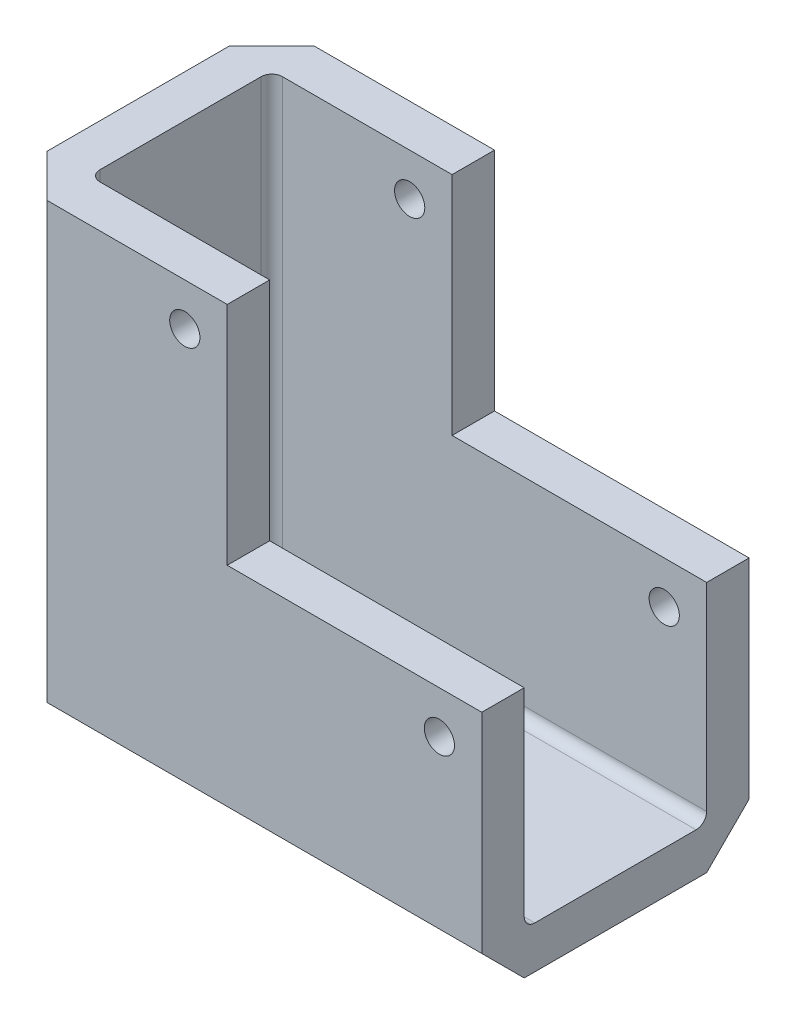
SolidWorks part; units mm, degrees
ref_plane "Alzado" through (0, 0, 0) normal (0, 0, 1) x (1, 0, 0)
ref_plane "Planta" through (0, 0, 0) normal (0, 1, 0) x (1, 0, 0)
ref_plane "Vista lateral" through (0, 0, 0) normal (1, 0, 0) x (0, 0, -1)
sketch "Croquis1" plane through (0, 0, 0) normal (0, 0, 1) x (1, 0, 0)
  line L0 (0, 0) -> (0, 21.3)
  line L1 (0, 21.3) -> (-17, 21.3)
  line L2 (-17, 21.3) -> (-17, -19.7)
  line L3 (-17, -19.7) -> (24, -19.7)
  line L4 (24, -19.7) -> (24, 0)
  line L5 (24, 0) -> (0, 0)
  dimension "D1" = 41
  dimension "D2" = 17
  dimension "D3" = 19.7
  dimension "D4" = 41
extrude "Saliente-Extruir1" add sketch "Croquis1" along normal blind 4
sketch "Croquis2" plane through (-17, 0, 0) normal (-1, 0, 0) x (0, 0, 1)
  line L0 (4, -19.7) -> (0, -19.7) construction
  line L1 (0, 21.3) -> (-17.2, 21.3)
  line L2 (0, 21.3) -> (0, -19.7)
  line L3 (0, -19.7) -> (-17.2, -19.7)
  line L4 (-17.2, 21.3) -> (-17.2, -19.7)
  line L6 (0, -19.7) -> (4, -19.7)
  line L7 (0, -19.7) -> (0, 21.3)
  line L8 (0, 21.3) -> (4, 21.3)
  line L9 (4, -19.7) -> (4, 21.3)
  line M9 (0, 21.3) -> (0, -19.7)
  line M10 (0, -19.7) -> (4, -19.7)
  line M11 (4, -19.7) -> (4, 21.3)
  line M12 (4, 21.3) -> (0, 21.3)
  dimension "D1" = 17.2
extrude "Saliente-Extruir2" add sketch "Croquis2" along normal blind 4 contours L1 L4 L3 M9 | M12 M9 M10 M11
sketch "Croquis3" plane through (0, -19.7, 0) normal (0, -1, 0) x (1, 0, 0)
  line L1 (-21, -17.2) -> (24, -17.2)
  line L2 (-21, -17.2) -> (-21, 4)
  line L3 (-21, 4) -> (24, 4)
  line L4 (24, -17.2) -> (24, 4)
extrude "Saliente-Extruir3" add sketch "Croquis3" along normal blind 4
sketch "Croquis4" plane through (0, 0, -17.2) normal (0, 0, -1) x (-1, 0, 0)
  line L0 (-24, -23.7) -> (-24, 0)
  line L1 (-24, 0) -> (0, 0)
  line L2 (0, 0) -> (0, 21.3)
  line L3 (0, 21.3) -> (21, 21.3)
  line L4 (21, 21.3) -> (21, -23.7)
  line L5 (21, -23.7) -> (-24, -23.7)
extrude "Saliente-Extruir4" add sketch "Croquis4" along normal blind 4
fillet "Redondeo1" radius 1 5 edges at (-17, 0.8, 0) (-17, 0.8, -17.2) (3.5, -19.7, -17.2) (3.5, -19.7, 0) (-17, -19.7, -8.6)
chamfer "Chaflán1" distance 4 angle 45 4 edges at (1.5, -23.7, 4) (-21, -1.2, -21.2) (-21, -1.2, 4) (1.5, -23.7, -21.2)
sketch "Croquis5" plane through (0, 0, -21.2) normal (0, 0, -1) x (-1, 0, 0)
  line L0 (-28, -16) -> (-20, -16) construction
  line L1 (-24, 0) -> (-24, -19.7) construction
  line L2 (-28, -14.5) -> (-20, -14.5)
  line L3 (-28, -17.5) -> (-20, -17.5)
  line L4 (-24, -19.7) -> (17, -19.7) construction
  arc A0 (-28, -14.5) -> (-28, -17.5) centre (-28, -16) ccw
  arc A1 (-20, -17.5) -> (-20, -14.5) centre (-20, -16) ccw
  point P4 (-24, -16)
  dimension "D1" = 3.7
  dimension "D2" = 3
  dimension "D3" = 8
extrude "Cortar-Extruir1" [suppressed] cut sketch "Croquis5" against normal up to next
sketch "Croquis6" plane through (0, 0, -21.2) normal (0, 0, -1) x (-1, 0, 0)
  line L0 (-24, -4) -> (4, -4) construction
  line L1 (-24, 0) -> (-24, -19.7) construction
  line L2 (4, -4) -> (4, 21.3) construction
  line L3 (17, 21.3) -> (0, 21.3) construction
  line L4 (0, 0) -> (-24, 0) construction
  line L5 (0, 21.3) -> (0, 0) construction
  circle A0 centre (-20, -4) radius 1.425
  circle A1 centre (4, 17.3) radius 1.425
  dimension "D3" = 2.85
  dimension "D1" = 4
  dimension "D2" = 4
  dimension "D4" = 4
  dimension "D5" = 4
extrude "Cortar-Extruir2" cut sketch "Croquis6" against normal through all
sketch "Croquis9" [suppressed] plane through (24, 0, 0) normal (1, 0, 0) x (0, 0, -1)
  line L1 (17.2, -14.5) -> (21.2, -14.5)
  line L2 (17.2, -14.5) -> (17.2, -17.5)
  line L3 (17.2, -17.5) -> (21.2, -17.5)
  line L4 (21.2, -14.5) -> (21.2, -17.5)
extrude "Saliente-Extruir5" [suppressed] add sketch "Croquis9" against normal blind 1
ref_plane "Plano1" [suppressed] through (0, 0, -8.7) normal (0, 0, -1) x (-1, 0, 0)
mirror "Simetría1" [suppressed] about plane through (0, 0, -8.7) normal (0, 0, -1)
sketch "Croquis11" plane through (0, 0, -21.2) normal (0, 0, -1) x (-1, 0, 0)
  line L1 (-24, 0) -> (17, 0)
  line L2 (-24, 0) -> (-24, -19.7)
  line L3 (-24, -19.7) -> (17, -19.7)
  line L4 (17, 0) -> (17, -19.7)
  line L5 (17, -19.7) -> (0, -19.7)
  line L6 (17, -19.7) -> (17, 21.3)
  line L7 (17, 21.3) -> (0, 21.3)
  line L8 (0, -19.7) -> (0, 21.3)
extrude "Saliente-Extruir6" [suppressed] add sketch "Croquis11" against normal blind 4
